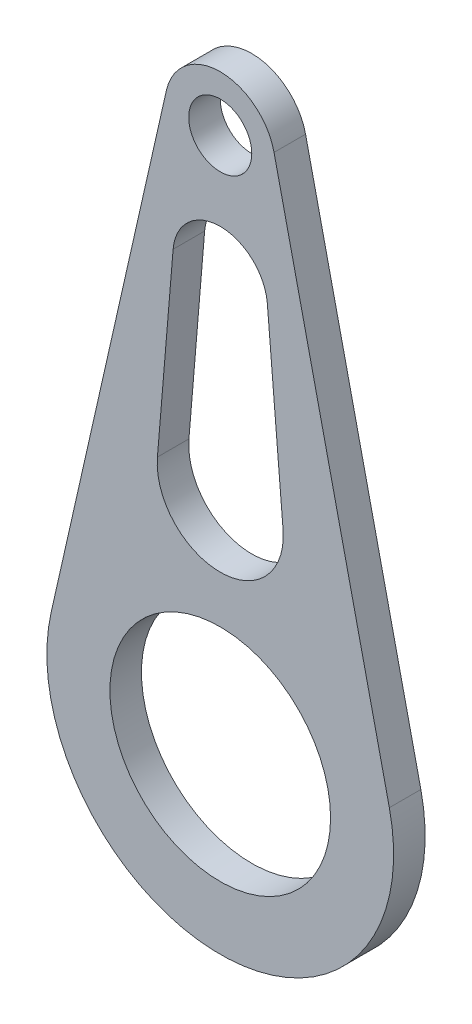
SolidWorks part; units mm, degrees
ref_plane "前视基准面" through (0, 0, 0) normal (0, 0, 1) x (1, 0, 0)
ref_plane "上视基准面" through (0, 0, 0) normal (0, 1, 0) x (1, 0, 0)
ref_plane "右视基准面" through (0, 0, 0) normal (1, 0, 0) x (0, 0, -1)
sketch "草图1" plane through (0, 0, 0) normal (0, 0, 1) x (1, 0, 0)
  line L0 (-3.4138, 34.7721) -> (-10.729, 2.4265)
  line L1 (0, -30.5072) -> (0, 63.4722) construction
  line L2 (3.4138, 34.7721) -> (10.729, 2.4265)
  line L3 (-2.9896, 26.25) -> (-3.9861, 14.3333)
  line L4 (2.9896, 26.25) -> (3.9861, 14.3333)
  circle A0 centre (0, 0) radius 7
  arc A1 (3.4138, 34.7721) -> (-3.4138, 34.7721) centre (0, 34) ccw
  arc A2 (2.9896, 26.25) -> (-2.9896, 26.25) centre (0, 26) ccw
  arc A3 (-3.9861, 14.3333) -> (3.9861, 14.3333) centre (0, 14) ccw
  circle A4 centre (0, 34) radius 2
  arc A5 (-10.729, 2.4265) -> (10.729, 2.4265) centre (0, 0) ccw
  dimension "D1" = 14
  dimension "D2" = 7
  dimension "D4" = 4
  dimension "D5" = 3
  dimension "D6" = 8
  dimension "D8" = 22
  dimension "D3" = 34
  dimension "D7" = 14
  dimension "D9" = 26
extrude "凸台-拉伸1" add sketch "草图1" along normal blind 2
